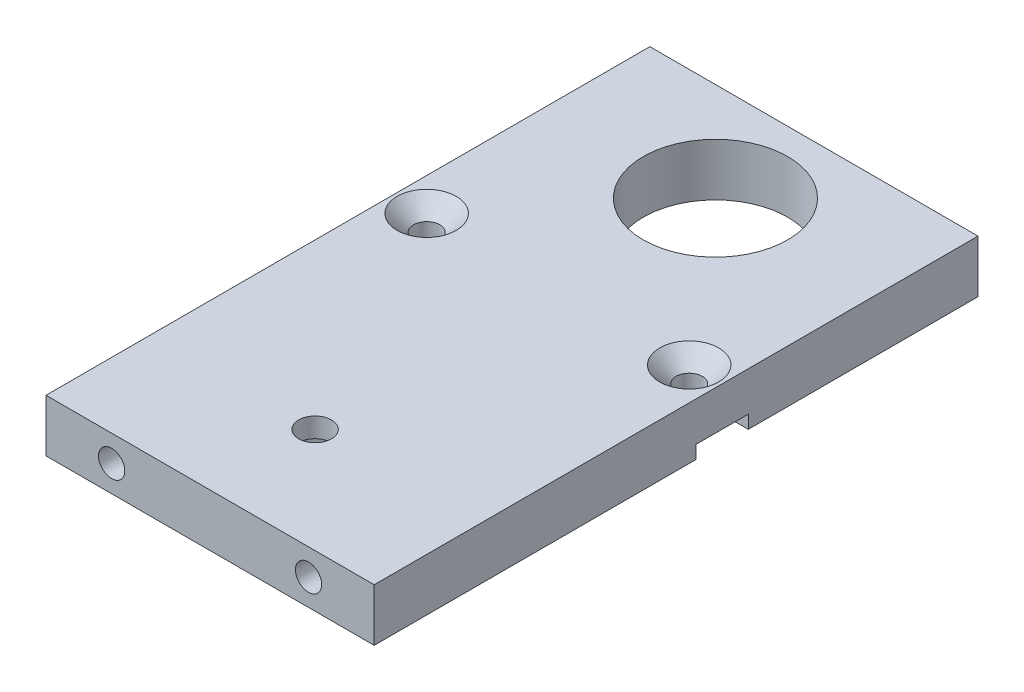
SolidWorks part; units mm, degrees
material "PVC rigide"
ref_plane "Plan de face" through (0, 0, 0) normal (0, 0, 1) x (1, 0, 0)
ref_plane "Plan de dessus" through (0, 0, 0) normal (0, 1, 0) x (1, 0, 0)
ref_plane "Plan de droite" through (0, 0, 0) normal (1, 0, 0) x (0, 0, -1)
sketch "Esquisse1" plane through (0, 0, 0) normal (0, 1, 0) x (1, 0, 0)
  line L0 (-6.4914, -72.1179) -> (-6.4914, 19.8821) construction
  line L1 (-31.4914, 19.8821) -> (18.5086, 19.8821)
  line L2 (-31.4914, 19.8821) -> (-31.4914, -72.1179)
  line L3 (-31.4914, -72.1179) -> (18.5086, -72.1179)
  line L4 (18.5086, 19.8821) -> (18.5086, -72.1179)
  line L6 (-41.3411, -19.1179) -> (33.4874, -19.1179) construction
  circle A1 centre (-6.4914, 4.8821) radius 11
  circle A2 centre (-26.4914, -19.1179) radius 2
  circle A3 centre (13.5086, -19.1179) radius 2
  dimension "D5" = 22
  dimension "D10" = 4
  dimension "D1" = 50
  dimension "D2" = 92
  dimension "D6" = 15
  dimension "D7" = 53
  dimension "D8" = 5
  dimension "D9" = 5
extrude "Boss.-Extru.1" add sketch "Esquisse1" along normal blind 8
chamfer "Chanfrein1" distance 2.5 angle 45 2 edges at (13.5086, 8, 21.1179) (-26.4914, 8, 21.1179)
sketch "Esquisse2" plane through (0, 0, 72.1179) normal (0, 0, 1) x (1, 0, 0)
  line L0 (-31.4914, 4) -> (18.5086, 4) construction
  line L1 (-31.4914, 8) -> (-31.4914, 0) construction
  line L2 (18.5086, 8) -> (18.5086, 0) construction
  circle A0 centre (-21.4914, 4) radius 2
  circle A1 centre (8.5086, 4) radius 2
  dimension "D1" = 4
  dimension "D2" = 10
  dimension "D3" = 10
extrude "Enlèv. mat.-Extru.1" cut sketch "Esquisse2" against normal blind 10
sketch "Esquisse3" plane through (0, 0, 0) normal (0, -1, 0) x (1, 0, 0)
  line L0 (-31.4914, 56.1179) -> (18.5086, 56.1179) construction
  line L1 (-31.4914, -19.8821) -> (-31.4914, 72.1179) construction
  line L2 (18.5086, 72.1179) -> (18.5086, -19.8821) construction
  line L3 (-31.4914, 72.1179) -> (18.5086, 72.1179) construction
  circle A0 centre (-6.4914, 56.1179) radius 8
  dimension "D2" = 16
  dimension "D1" = 16
extrude "Enlèv. mat.-Extru.2" cut sketch "Esquisse3" against normal blind 5
sketch "Esquisse4" plane through (0, 5, 0) normal (0, -1, 0) x (1, 0, 0)
  circle A0 centre (-6.4914, 56.1179) radius 2.5
  circle A1 centre (-6.4914, 56.1179) radius 8 construction
  dimension "D1" = 5
extrude "Enlèv. mat.-Extru.3" cut sketch "Esquisse4" against normal through all
sketch "Esquisse5" plane through (0, 0, 0) normal (0, -1, 0) x (1, 0, 0)
  line L0 (18.5086, 72.1179) -> (18.5086, -19.8821) construction
  line L1 (18.5086, 15.1179) -> (-31.4914, 15.1179)
  line L2 (18.5086, 15.1179) -> (18.5086, 23.1179)
  line L3 (18.5086, 23.1179) -> (-31.4914, 23.1179)
  line L4 (-31.4914, 15.1179) -> (-31.4914, 23.1179)
  circle A0 centre (13.5086, 19.1179) radius 2 construction
  dimension "D1" = 4
  dimension "D2" = 8
extrude "Enlèv. mat.-Extru.4" cut sketch "Esquisse5" against normal blind 2
